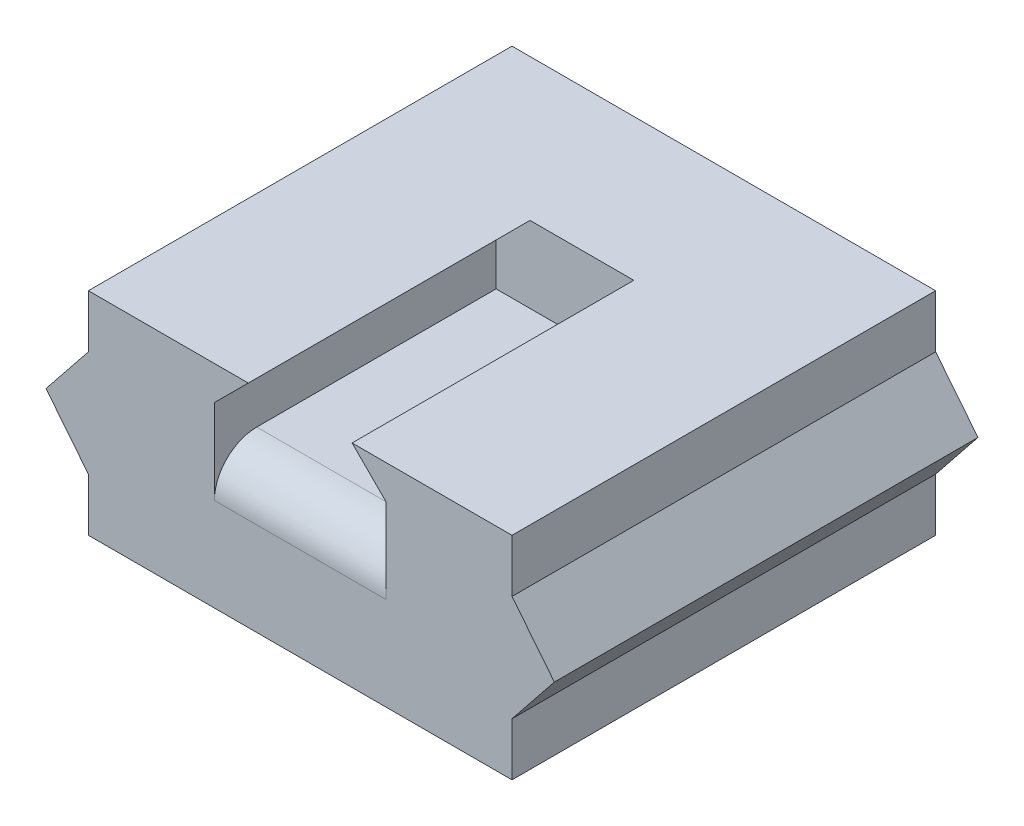
SolidWorks part; units mm, degrees
ref_plane "前视基准面" through (0, 0, 0) normal (0, 0, 1) x (1, 0, 0)
ref_plane "上视基准面" through (0, 0, 0) normal (0, 1, 0) x (1, 0, 0)
ref_plane "右视基准面" through (0, 0, 0) normal (1, 0, 0) x (0, 0, -1)
sketch "草图1" plane through (0, 0, 0) normal (0, 1, 0) x (1, 0, 0)
  line L1 (-5, -5) -> (5, -5)
  line L2 (-5, -5) -> (-5, 5)
  line L3 (-5, 5) -> (5, 5)
  line L4 (5, -5) -> (5, 5)
  line L5 (-5, -5) -> (5, 5) construction
  line L6 (-5, 5) -> (5, -5) construction
  point P0 (0, 0)
  dimension "D1" = 10
  dimension "D2" = 10
extrude "凸台-拉伸1" add sketch "草图1" along normal blind 5
sketch "草图2" plane through (0, 0, -5) normal (0, 0, -1) x (-1, 0, 0)
  line L0 (5, 2.5) -> (7, 2.5) construction
  line L1 (5, 5) -> (5, 0) construction
  line L2 (5, 1.25) -> (5, 3.75)
  line L3 (5, 3.75) -> (6, 2.5)
  line L4 (5, 1.25) -> (6, 2.5)
  line L5 (0, 0) -> (0, 3.5842) construction
  line L6 (-5, 0) -> (5, 0) construction
  line L7 (-5, 1.25) -> (-5, 3.75)
  line L8 (-5, 1.25) -> (-6, 2.5)
  line L9 (-5, 3.75) -> (-6, 2.5)
  dimension "D1" = 2.5
  dimension "D2" = 1
extrude "凸台-拉伸2" add sketch "草图2" against normal up to surface (10 mm away) up to face at (0, 2.5, 5)
sketch "草图3" plane through (0, 5, 0) normal (0, 1, 0) x (1, 0, 0)
  line L1 (-2.025, -1.65) -> (2.025, -1.65)
  line L2 (-2.025, -1.65) -> (-2.025, 1.65)
  line L3 (-2.025, 1.65) -> (2.025, 1.65)
  line L4 (2.025, -1.65) -> (2.025, 1.65)
  line L5 (-2.025, -1.65) -> (2.025, 1.65) construction
  line L6 (-2.025, 1.65) -> (2.025, -1.65) construction
  point P0 (0, 0)
  dimension "D1" = 4.05
  dimension "D2" = 3.3
extrude "切除-拉伸1" cut sketch "草图3" against normal blind 1.8
sketch "草图4" plane through (0, 0, 1.65) normal (0, 0, -1) x (-1, 0, 0)
  line L4 (2.025, 5) -> (-2.025, 5)
  line L5 (-2.025, 5) -> (-2.025, 3.2)
  line L6 (-2.025, 3.2) -> (2.025, 3.2)
  line L7 (2.025, 3.2) -> (2.025, 5)
  line L8 (2.025, 5) -> (-2.025, 5)
  line L9 (-2.025, 5) -> (-2.025, 3.2)
  line L10 (-2.025, 3.2) -> (2.025, 3.2)
  line L11 (2.025, 3.2) -> (2.025, 5)
  dimension "D1" = 0
extrude "切除-拉伸2" cut sketch "草图4" against normal through all
fillet "圆角1" radius 1 1 edges at (0, 3.2, 5)
sketch "草图5" plane through (0, 0, -1.65) normal (0, 0, 1) x (1, 0, 0)
  line L0 (2.025, 5) -> (2.025, 4.2)
  line L1 (2.025, 3.2) -> (2.025, 5) construction
  line L2 (2.025, 4.2) -> (1.225, 5)
  line L3 (2.025, 5) -> (-2.025, 5) construction
  line L4 (1.225, 5) -> (2.025, 5)
  line L5 (0, 3.2) -> (0, 6.0972) construction
  line L6 (2.025, 3.2) -> (-2.025, 3.2) construction
  line L7 (-2.025, 4.2) -> (-1.225, 5)
  line L8 (-2.025, 5) -> (-2.025, 4.2)
  line L9 (-1.225, 5) -> (-2.025, 5)
  dimension "D1" = 45
  dimension "D2" = 0.8
extrude "凸台-拉伸3" add sketch "草图5" along normal up to surface (6.65 mm away) up to face at (0, 2.8143, 5)
